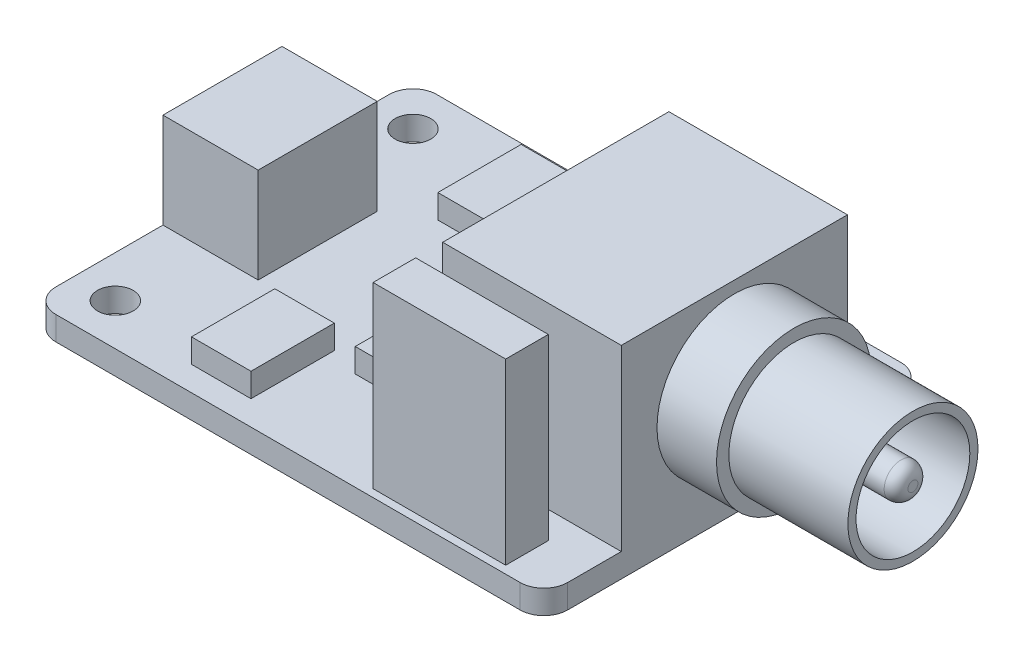
SolidWorks part; units mm, degrees
ref_plane "Front Plane" through (0, 0, 0) normal (0, 0, 1) x (1, 0, 0)
ref_plane "Top Plane" through (0, 0, 0) normal (0, 1, 0) x (1, 0, 0)
ref_plane "Right Plane" through (0, 0, 0) normal (1, 0, 0) x (0, 0, -1)
sketch "Sketch1" plane through (0, 0, 0) normal (0, 1, 0) x (1, 0, 0)
  line L1 (-179.1905, 78.9286) -> (-136.1905, 78.9286)
  line L2 (-179.1905, 78.9286) -> (-179.1905, 46.9286)
  line L3 (-179.1905, 46.9286) -> (-136.1905, 46.9286)
  line L4 (-136.1905, 78.9286) -> (-136.1905, 46.9286)
  circle A0 centre (-175.6905, 75.4286) radius 1.5
  circle A1 centre (-175.6905, 50.4286) radius 1.5
  dimension "D3" = 3
  dimension "D4" = 3
  dimension "D7" = 3.5
  dimension "D8" = 3.5
  dimension "D9" = 3.5
  dimension "D10" = 3.5
  dimension "D1" = 43
  dimension "D2" = 32
extrude "Boss-Extrude1" add sketch "Sketch1" along normal blind 2
fillet "Fillet1" radius 2 4 edges at (-179.1905, 1, -78.9286) (-136.1905, 1, -78.9286) (-136.1905, 1, -46.9286) (-179.1905, 1, -46.9286)
sketch "Sketch2" plane through (0, 2, 0) normal (0, 1, 0) x (1, 0, 0)
  line L0 (-179.1905, 76.9286) -> (-179.1905, 48.9286) construction
  line L1 (-195.986, 57.9286) -> (-187.986, 57.9286)
  line L2 (-195.986, 57.9286) -> (-195.986, 67.9286)
  line L3 (-195.986, 67.9286) -> (-187.986, 67.9286)
  line L4 (-187.986, 57.9286) -> (-187.986, 67.9286)
  line L6 (-151.1905, 53.4286) -> (-136.1905, 53.4286)
  line L7 (-151.1905, 53.4286) -> (-151.1905, 72.4286)
  line L8 (-151.1905, 72.4286) -> (-136.1905, 72.4286)
  line L9 (-136.1905, 53.4286) -> (-136.1905, 72.4286)
  line L10 (-136.1905, 48.9286) -> (-136.1905, 76.9286) construction
  line L11 (-177.1905, 46.9286) -> (-138.1905, 46.9286) construction
  line L12 (-138.1905, 78.9286) -> (-177.1905, 78.9286) construction
  line L14 (-151.1905, 51.1605) -> (-140.0499, 51.1605)
  line L15 (-151.1905, 51.1605) -> (-151.1905, 47.5777)
  line L16 (-151.1905, 47.5777) -> (-140.0499, 47.5777)
  line L17 (-140.0499, 51.1605) -> (-140.0499, 47.5777)
  point P4 (-195.986, 62.9286)
  point P7 (-179.1905, 62.9286)
  line M14 (-136.1905, 48.9286) -> (-136.1905, 76.9286)
  dimension "D1" = 10
  dimension "D2" = 8
  dimension "D4" = 15
  dimension "D5" = 6.5
  dimension "D6" = 6.5
extrude "Boss-Extrude2" add sketch "Sketch2" along normal blind 15 contours L8 L7 L6 M14 | L17 L14 L15 L16
sketch "Sketch3" plane through (0, 2, 0) normal (0, 1, 0) x (1, 0, 0)
  line L0 (-179.1905, 76.9286) -> (-179.1905, 48.9286) construction
  line L1 (-171.1905, 57.9286) -> (-179.1905, 57.9286)
  line L2 (-171.1905, 57.9286) -> (-171.1905, 67.9286)
  line L3 (-171.1905, 67.9286) -> (-179.1905, 67.9286)
  line L4 (-179.1905, 57.9286) -> (-179.1905, 67.9286)
  point P4 (-179.1905, 62.9286)
  point P7 (-179.1905, 62.9286)
  dimension "D1" = 8
  dimension "D2" = 10
extrude "Boss-Extrude3" add sketch "Sketch3" along normal blind 8
sketch "Sketch4" plane through (0, 2, 0) normal (0, 1, 0) x (1, 0, 0)
  line L1 (-155.2818, 71.9845) -> (-160.2818, 71.9845)
  line L2 (-155.2818, 71.9845) -> (-155.2818, 64.9845)
  line L3 (-155.2818, 64.9845) -> (-160.2818, 64.9845)
  line L4 (-160.2818, 71.9845) -> (-160.2818, 64.9845)
  line L5 (-155.2818, 62.1725) -> (-160.2818, 62.1725)
  line L6 (-155.2818, 62.1725) -> (-155.2818, 55.1725)
  line L7 (-155.2818, 55.1725) -> (-160.2818, 55.1725)
  line L8 (-160.2818, 62.1725) -> (-160.2818, 55.1725)
  line L9 (-163.0126, 76.8418) -> (-168.0126, 76.8418)
  line L10 (-163.0126, 76.8418) -> (-163.0126, 69.8418)
  line L11 (-163.0126, 69.8418) -> (-168.0126, 69.8418)
  line L12 (-168.0126, 76.8418) -> (-168.0126, 69.8418)
  line L13 (-162.8613, 55.9959) -> (-167.8613, 55.9959)
  line L14 (-162.8613, 55.9959) -> (-162.8613, 48.9959)
  line L15 (-162.8613, 48.9959) -> (-167.8613, 48.9959)
  line L16 (-167.8613, 55.9959) -> (-167.8613, 48.9959)
  dimension "D1" = 5
  dimension "D2" = 7
  dimension "D3" = 5
  dimension "D4" = 7
  dimension "D5" = 5
  dimension "D6" = 7
  dimension "D7" = 5
  dimension "D8" = 7
extrude "Boss-Extrude4" add sketch "Sketch4" along normal blind 2
sketch "Sketch5" plane through (-179.1905, 0, 0) normal (-1, 0, 0) x (0, 0, 1)
  line L0 (-67.9286, 10) -> (-57.9286, 10) construction
  line L1 (-66.9286, 9) -> (-58.9286, 9)
  line L2 (-66.9286, 9) -> (-66.9286, 3)
  line L3 (-66.9286, 3) -> (-58.9286, 3)
  line L4 (-58.9286, 9) -> (-58.9286, 3)
  line L5 (-57.9286, 10) -> (-57.9286, 2) construction
  line L6 (-67.9286, 2) -> (-76.9286, 2) construction
  line L7 (-67.9286, 10) -> (-67.9286, 2) construction
  line L9 (-65.7286, 6.5) -> (-64.7286, 6.5)
  line L10 (-65.7286, 6.5) -> (-65.7286, 5.5)
  line L11 (-65.7286, 5.5) -> (-64.7286, 5.5)
  line L12 (-64.7286, 6.5) -> (-64.7286, 5.5)
  line L13 (-63.4286, 6.5) -> (-62.4286, 6.5)
  line L14 (-63.4286, 6.5) -> (-63.4286, 5.5)
  line L15 (-63.4286, 5.5) -> (-62.4286, 5.5)
  line L16 (-62.4286, 6.5) -> (-62.4286, 5.5)
  line L17 (-61.1286, 6.5) -> (-60.1286, 6.5)
  line L18 (-61.1286, 6.5) -> (-61.1286, 5.5)
  line L19 (-61.1286, 5.5) -> (-60.1286, 5.5)
  line L20 (-60.1286, 6.5) -> (-60.1286, 5.5)
  point P24 (-65.2286, 6.5)
  dimension "D1" = 1
  dimension "D2" = 1
  dimension "D3" = 1
  dimension "D4" = 1
  dimension "D5" = 1
  dimension "D6" = 1
  dimension "D7" = 1
  dimension "D8" = 1
  dimension "D9" = 1
  dimension "D10" = 1
  dimension "D11" = 2.5
  dimension "D12" = 2.5
  dimension "D13" = 2.5
  dimension "D14" = 1.2
  dimension "D15" = 1.2
  dimension "D16" = 1.3
extrude "Cut-Extrude1" cut sketch "Sketch5" against normal blind 7
draft "Draft1" type of draft neutral plane draft angle 1 faces to draft 3 face at (-179.1905, 6, -65.2286) face at (-179.1905, 6, -60.6286) face at (-179.1905, 6, -62.9286) neutral plane through (-172.1905, 6.5, -63.4286) neutral plane normal (0, 1, 0) parameters "D1"=1
chamfer "Chamfer1" distance 2.5 angle 8 12 edges at (-179.2079, 5.5, -60.6286) (-179.1992, 6, -60.1286) (-179.1905, 6.5, -60.6286) (-179.1992, 6, -61.1286) (-179.2079, 5.5, -62.9286) (-179.1992, 6, -62.4286) (-179.1905, 6.5, -62.9286) (-179.1992, 6, -63.4286) (-179.1992, 6, -65.7286) (-179.2079, 5.5, -65.2286) (-179.1992, 6, -64.7286) (-179.1905, 6.5, -65.2286)
sketch "Sketch6" plane through (-136.1905, 0, 0) normal (1, 0, 0) x (0, 0, -1)
  line L0 (53.4286, 17) -> (72.4286, 17) construction
  circle A0 centre (62.9286, 9.5) radius 6.5
  point P6 (62.9286, 17)
  dimension "D1" = 13
  dimension "D2" = 7.5
extrude "Boss-Extrude5" add sketch "Sketch6" along normal blind 5
sketch "Sketch7" plane through (-131.1905, 0, 0) normal (1, 0, 0) x (0, 0, -1)
  circle A0 centre (62.9286, 9.5) radius 5.4647
  circle A1 centre (62.9286, 9.5) radius 6.5 construction
  dimension "D1" = 0
extrude "Boss-Extrude6" add sketch "Sketch7" along normal blind 10
sketch "Sketch8" plane through (-121.1905, 0, 0) normal (1, 0, 0) x (0, 0, -1)
  circle A0 centre (62.9286, 9.5) radius 4.7788
  circle A1 centre (62.9286, 9.5) radius 1.4184
extrude "Cut-Extrude2" cut sketch "Sketch8" against normal blind 15
fillet "Fillet3" radius 1 1 edges at (-121.1905, 9.5, -64.347)
